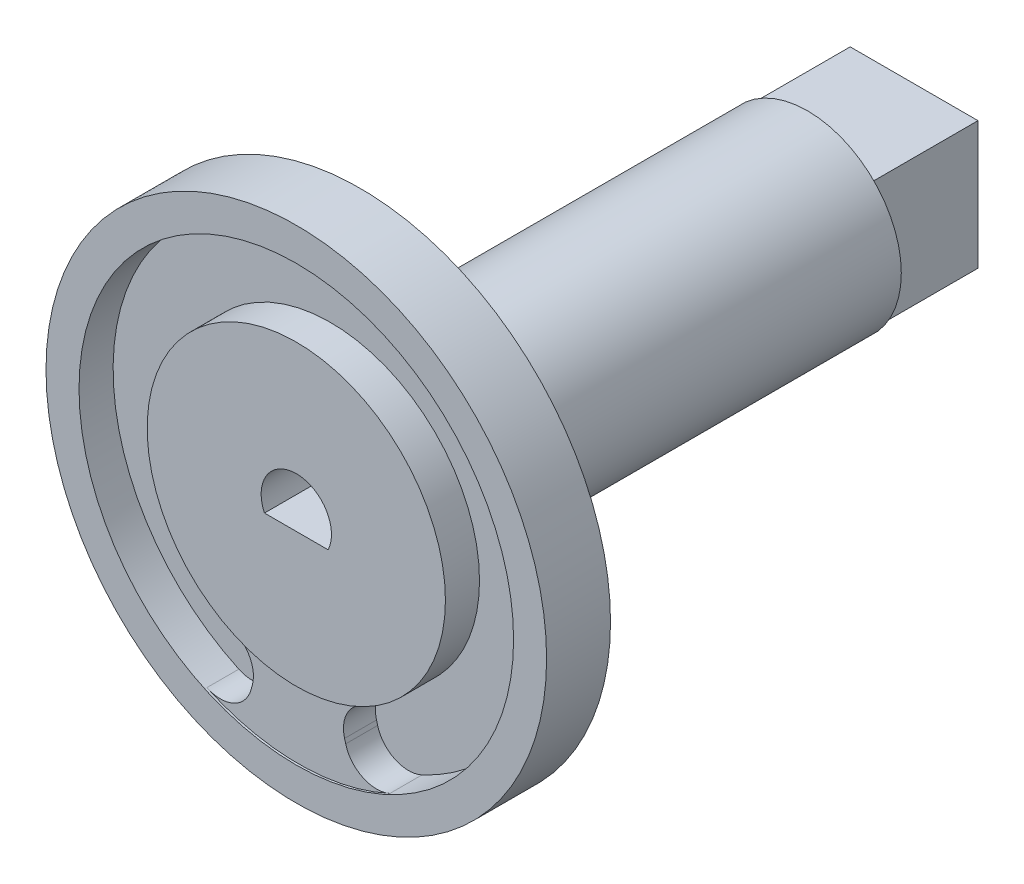
SolidWorks part; units mm, degrees
ref_plane "前视基准面" through (0, 0, 0) normal (0, 0, 1) x (1, 0, 0)
ref_plane "上视基准面" through (0, 0, 0) normal (0, 1, 0) x (1, 0, 0)
ref_plane "右视基准面" through (0, 0, 0) normal (1, 0, 0) x (0, 0, -1)
sketch "草图1" plane through (0, 0, 0) normal (0, 0, 1) x (1, 0, 0)
  circle A0 centre (0, 0) radius 11.75
  dimension "D1" = 23.5
extrude "凸台-拉伸1" add sketch "草图1" along normal blind 3
sketch "草图2" plane through (0, 0, 0) normal (0, 0, -1) x (-1, 0, 0)
  line L1 (1.4292, -0.6) -> (-1.4292, -0.6)
  arc A0 (1.4292, -0.6) -> (-1.4292, -0.6) centre (0, 0) ccw
  dimension "D1" = 3.1
  dimension "D2" = 0.6
extrude "切除-拉伸1" cut sketch "草图2" against normal blind 13
sketch "草图3" plane through (0, 0, 3) normal (0, 0, 1) x (1, 0, 0)
  circle A0 centre (0, 0) radius 7
  circle A1 centre (0, 0) radius 10.2
  dimension "D1" = 14
  dimension "D2" = 20.4
extrude "切除-拉伸2" cut sketch "草图3" against normal blind 1.6
sketch "草图4" plane through (0, 0, 1.4) normal (0, 0, 1) x (1, 0, 0)
  line L0 (1.8117, -6.7615) -> (2.64, -9.8524)
  line L1 (-1.8117, -6.7615) -> (-2.64, -9.8524)
  arc A0 (-1.8117, -6.7615) -> (1.8117, -6.7615) centre (0, 0) ccw
  circle A1 centre (0, 0) radius 7 construction
  arc A2 (-2.64, -9.8524) -> (2.64, -9.8524) centre (0, 0) ccw
  circle A3 centre (0, 0) radius 10.2 construction
  dimension "D1" = 30
  dimension "D2" = 30
extrude "凸台-拉伸2" add sketch "草图4" along normal blind 1.5
fillet "圆角1" radius 1.5 4 edges at (-2.64, -9.8524, 2.15) (-1.8117, -6.7615, 2.15) (2.64, -9.8524, 2.15) (1.8117, -6.7615, 2.15)
sketch "草图5" [suppressed] plane through (0, 0, 3) normal (0, 0, 1) x (1, 0, 0)
  circle A1 centre (0, 0) radius 7
  circle A2 centre (0, 0) radius 7
  dimension "D1" = 0
sketch "草图6" plane through (0, 0, 3) normal (0, 0, 1) x (1, 0, 0)
  line L0 (-1.4292, -0.6) -> (1.4292, -0.6) construction
  line L1 (-1.4292, -0.6) -> (1.4292, -0.6)
  arc A1 (1.4292, -0.6) -> (-1.4292, -0.6) centre (0, 0) ccw construction
  arc A2 (1.4292, -0.6) -> (-1.4292, -0.6) centre (0, 0) ccw
  circle A3 centre (0, 0) radius 3
  dimension "D1" = 6
extrude "凸台-拉伸3" [suppressed] add sketch "草图6" along normal blind 1.1
sketch "草图7" plane through (0, 0, 0) normal (0, 0, -1) x (-1, 0, 0)
  line L0 (-1.4292, -0.6) -> (1.4292, -0.6) construction
  line L1 (-1.4292, -0.6) -> (1.4292, -0.6)
  arc A0 (1.4292, -0.6) -> (-1.4292, -0.6) centre (0, 0) ccw construction
  arc A1 (1.4292, -0.6) -> (-1.4292, -0.6) centre (0, 0) ccw
  circle A2 centre (0, 0) radius 4.4
  dimension "D1" = 8.8
extrude "凸台-拉伸4" add sketch "草图7" along normal blind 2
sketch "草图8" plane through (0, 0, 0) normal (0, 0, -1) x (-1, 0, 0)
  circle A0 centre (0, 0) radius 4.25
  circle A1 centre (0, 0) radius 7
  dimension "D1" = 8.5
  dimension "D2" = 14
extrude "切除-拉伸3" [suppressed] cut sketch "草图8" against normal blind 1
sketch "草图9" plane through (0, 0, -2) normal (0, 0, -1) x (-1, 0, 0)
  circle A0 centre (0, 0) radius 4.4
  dimension "D1" = 8.8
extrude "凸台-拉伸5" add sketch "草图9" along normal blind 19
sketch "草图10" plane through (0, 0, -21) normal (0, 0, -1) x (-1, 0, 0)
  line L1 (-3, -3) -> (3, -3)
  line L2 (-3, -3) -> (-3, 3)
  line L3 (-3, 3) -> (3, 3)
  line L4 (3, -3) -> (3, 3)
  line L5 (-3, -3) -> (3, 3) construction
  line L6 (-3, 3) -> (3, -3) construction
  point P0 (0, 0)
  dimension "D1" = 6
  dimension "D2" = 6
  dimension "D3" = 6
extrude "凸台-拉伸6" add sketch "草图10" along normal blind 5
sketch "草图11" plane through (0, 0, 3) normal (0, 0, 1) x (1, 0, 0)
  line L0 (1.4292, -0.6) -> (-1.4292, -0.6) construction
  line L1 (1.4292, -0.6) -> (-1.4292, -0.6)
  line L2 (1.4942, -0.7) -> (-1.4942, -0.7)
  arc A0 (1.4292, -0.6) -> (-1.4292, -0.6) centre (0, 0) ccw construction
  arc A1 (1.4292, -0.6) -> (-1.4292, -0.6) centre (0, 0) ccw
  arc A2 (1.4942, -0.7) -> (-1.4942, -0.7) centre (0, 0) ccw
  dimension "D1" = 0.1
extrude "切除-拉伸4" cut sketch "草图11" against normal blind 10
